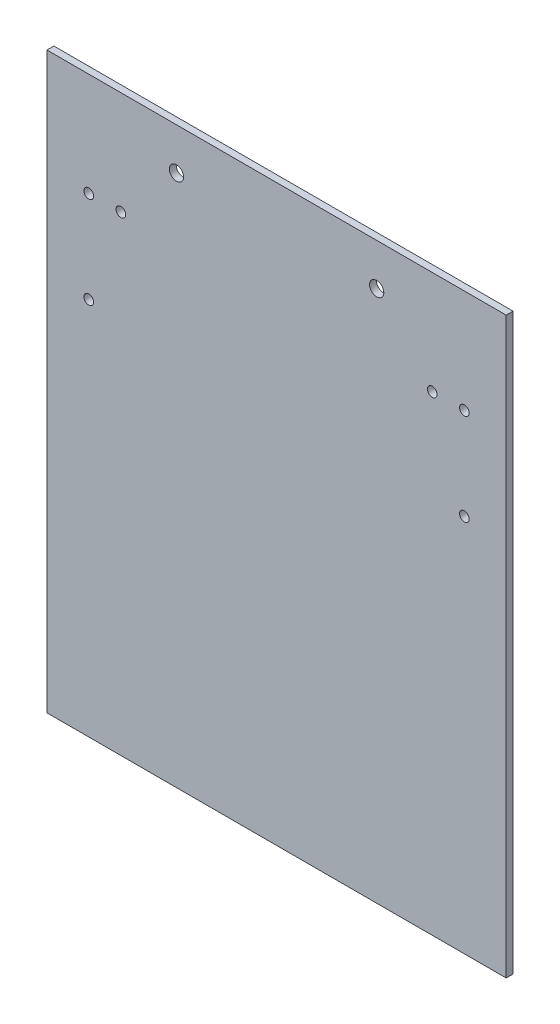
SolidWorks part; units mm, degrees
material "Stop 1060"
ref_plane "Płaszczyzna przednia" through (0, 0, 0) normal (0, 0, 1) x (1, 0, 0)
ref_plane "Płaszczyzna górna" through (0, 0, 0) normal (0, 1, 0) x (1, 0, 0)
ref_plane "Płaszczyzna prawa" through (0, 0, 0) normal (1, 0, 0) x (0, 0, -1)
sketch "Szkic1" plane through (0, 0, 0) normal (0, 0, 1) x (1, 0, 0)
  line L1 (0, 0) -> (200, 0)
  line L2 (0, 0) -> (0, 250)
  line L3 (0, 250) -> (200, 250)
  line L4 (200, 0) -> (200, 250)
  dimension "D1" = 200
  dimension "D2" = 250
extrude "Dodanie-wyciągnięcie1" add sketch "Szkic1" along normal blind 3
sketch "Szkic2" plane through (0, 0, 3) normal (0, 0, 1) x (1, 0, 0)
  line L0 (100, 250) -> (100, 124.0289) construction
  line L1 (200, 250) -> (0, 250) construction
  circle A0 centre (56.4, 231.8) radius 3.1
  circle A1 centre (32.2, 205) radius 2.1
  circle A2 centre (18.2, 205) radius 2.1
  circle A3 centre (18.2, 165) radius 2.1
  circle A4 centre (181.8, 165) radius 2.1
  circle A5 centre (181.8, 205) radius 2.1
  circle A6 centre (167.8, 205) radius 2.1
  circle A7 centre (143.6, 231.8) radius 3.1
extrude "Wytnij-wyciągnięcie1" cut sketch "Szkic2" against normal through all contours A3 | A0 | A7 | A6 | A5 | A2 | A1 | A4
